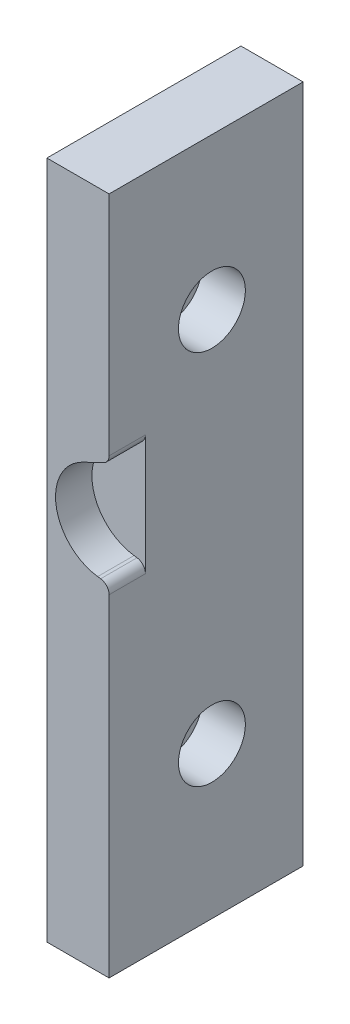
SolidWorks part; units mm, degrees
material "6061-T6 (SS)"
ref_plane "X-Y Datum" through (0, 0, 0) normal (0, 0, 1) x (1, 0, 0)
ref_plane "X-Z Datum" through (0, 0, 0) normal (0, 1, 0) x (1, 0, 0)
ref_plane "Y-Z Datum" through (0, 0, 0) normal (1, 0, 0) x (0, 0, -1)
sketch "Sketch1" plane through (0, 0, 0) normal (0, 0, 1) x (1, 0, 0)
  line L1 (8.1407, 88.9) -> (-8.1407, 88.9)
  line L6 (-8.1407, 88.9) -> (-8.1407, -88.9)
  line L7 (-8.1407, -88.9) -> (8.1407, -88.9)
  line L9 (8.1407, 88.9) -> (8.1407, -88.9)
  point P0 (8.1407, 0)
  point P2 (0, 88.9)
  dimension "D4" = 177.8
  dimension "D6" = 16.2814
extrude "Boss-Extrude1" add sketch "Sketch1" along normal mid plane 50.8
sketch "Sketch2" plane through (8.1407, 0, 0) normal (1, 0, 0) x (0, 0, -1)
  line L0 (1.524, 49.2117) -> (1.524, -49.2117) construction
  line L1 (25.4, -88.9) -> (25.4, 88.9) construction
  circle A0 centre (1.524, 49.2117) radius 6.7577
  circle A1 centre (1.524, -49.2117) radius 6.7577
  point P4 (1.524, 49.2117)
  point P5 (1.524, -49.2117)
  point P6 (25.4, 0)
  point P10 (1.524, 0)
  dimension "D2" = 13.5153
  dimension "D1" = 98.4235
  dimension "D3" = 23.876
extrude "Cut-Extrude1" cut sketch "Sketch2" against normal through all
sketch "Sketch3" plane through (8.1407, 0, 0) normal (1, 0, 0) x (0, 0, -1)
  circle A0 centre (1.524, 49.2117) radius 8.7641
  circle A1 centre (1.524, -49.2117) radius 8.7641
  dimension "D1" = 17.5282
extrude "Cut-Extrude2" cut sketch "Sketch3" against normal offset from surface (11.3284 mm away) 4.953 up to face at (-8.1407, 49.2117, -8.2817)
sketch "Sketch5" plane through (0, 0, 25.4) normal (0, 0, 1) x (1, 0, 0)
  line L0 (1.3843, 24.7021) -> (8.1407, 27.9012)
  line L1 (1.3843, 24.7021) -> (11.7942, 29.6311) construction
  line L3 (5.1478, 0.6342) -> (8.1407, 0.2369)
  line L4 (5.1478, 0.6342) -> (16.5655, -0.8816) construction
  line L5 (8.1407, 27.9012) -> (8.1407, 0.2369)
  line L6 (8.1407, -88.9) -> (8.1407, 88.9) construction
  arc A0 (1.3843, 24.7021) -> (5.1478, 0.6342) centre (6.8192, 13.2238) ccw construction
  arc A1 (1.3843, 24.7021) -> (5.1478, 0.6342) centre (6.8192, 13.2238) ccw
extrude "Cut-Extrude3" cut sketch "Sketch5" against normal blind 9.525
sketch "Sketch6" plane through (8.1407, 0, 0) normal (1, 0, 0) x (0, 0, -1)
  circle A0 centre (4.7498, -73.66) radius 5.715
  circle A1 centre (4.7498, 5.715) radius 5.715
fillet "Fillet1" radius 2.54 2 edges at (8.1407, 0.2369, 20.6375) (8.1407, 27.9012, 20.6375)
